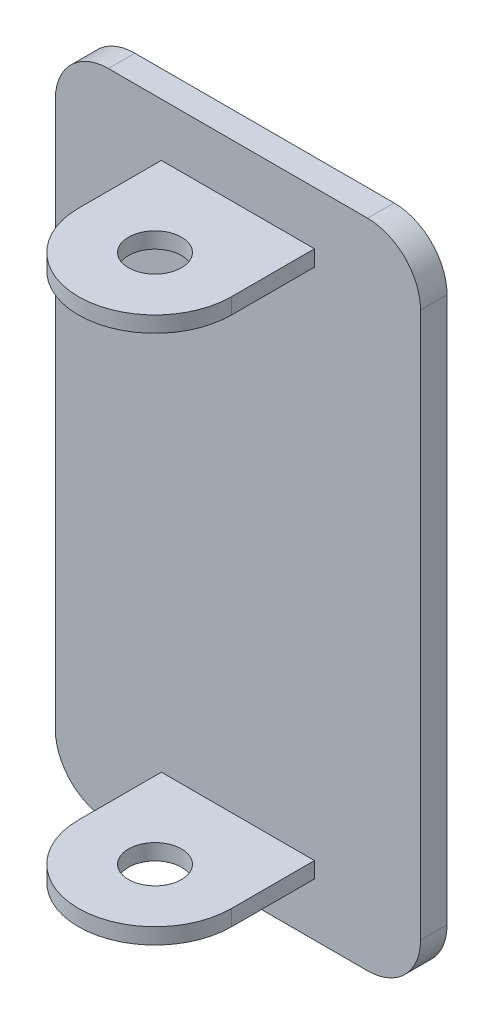
SolidWorks part; units mm, degrees
ref_plane "Front Plane" through (0, 0, 0) normal (0, 0, 1) x (1, 0, 0)
ref_plane "Top Plane" through (0, 0, 0) normal (0, 1, 0) x (1, 0, 0)
ref_plane "Right Plane" through (0, 0, 0) normal (1, 0, 0) x (0, 0, -1)
sketch "Sketch1" plane through (0, 0, 0) normal (0, 1, 0) x (1, 0, 0)
  line L0 (-28.8675, -84.3647) -> (0, -84.3647)
  line L1 (0, -84.3647) -> (0, -100)
  line L2 (-28.8675, -84.3647) -> (-28.8675, -100)
  arc A2 (-28.8675, -100) -> (0, -100) centre (-14.4338, -100) ccw
  circle A3 centre (-14.4338, -100) radius 5
  dimension "D4" = 10
extrude "Boss-Extrude1" add sketch "Sketch1" along normal blind 102.9
sketch "Sketch2" plane through (0, 0, 0) normal (0, 0, 1) x (1, 0, 0)
  line L0 (0, 102.9) -> (0, 0) construction
  line L1 (0, 99.9) -> (-28.8675, 99.9)
  line L2 (0, 99.9) -> (0, 3)
  line L3 (0, 3) -> (-28.8675, 3)
  line L4 (-28.8675, 99.9) -> (-28.8675, 3)
  line L5 (-28.8675, 102.9) -> (-28.8675, 0) construction
  line L6 (0, 102.9) -> (-28.8675, 102.9) construction
  line L7 (0, 0) -> (-28.8675, 0) construction
  dimension "D1" = 3
  dimension "D2" = 3
extrude "Cut-Extrude1" cut sketch "Sketch2" along normal blind 217
ref_plane "Plane1" through (0, 0, 84.3647) normal (0, 0, -1) x (-1, 0, 0)
sketch "Sketch5" plane through (0, 0, 84.3647) normal (0, 0, -1) x (-1, 0, 0)
  line L0 (0, 102.9) -> (28.8675, 102.9) construction
  line L1 (-10, 112.9) -> (38.8675, 112.9)
  line L2 (-20, 102.9) -> (-20, 0)
  line L3 (-10, -10) -> (38.8675, -10)
  line L4 (48.8675, 102.9) -> (48.8675, 0)
  line L5 (0, 0) -> (28.8675, 0) construction
  line L6 (28.8675, 3) -> (28.8675, 0) construction
  line L7 (0, 3) -> (0, 0) construction
  arc A0 (-20, 0) -> (-10, -10) centre (-10, 0) ccw
  arc A1 (38.8675, -10) -> (48.8675, 0) centre (38.8675, 0) ccw
  arc A2 (38.8675, 112.9) -> (48.8675, 102.9) centre (38.8675, 102.9) cw
  arc A3 (-10, 112.9) -> (-20, 102.9) centre (-10, 102.9) ccw
  dimension "D5" = 10
  dimension "D1" = 10
  dimension "D2" = 10
  dimension "D3" = 20
  dimension "D4" = 20
extrude "Boss-Extrude2" add sketch "Sketch5" along normal blind 5
